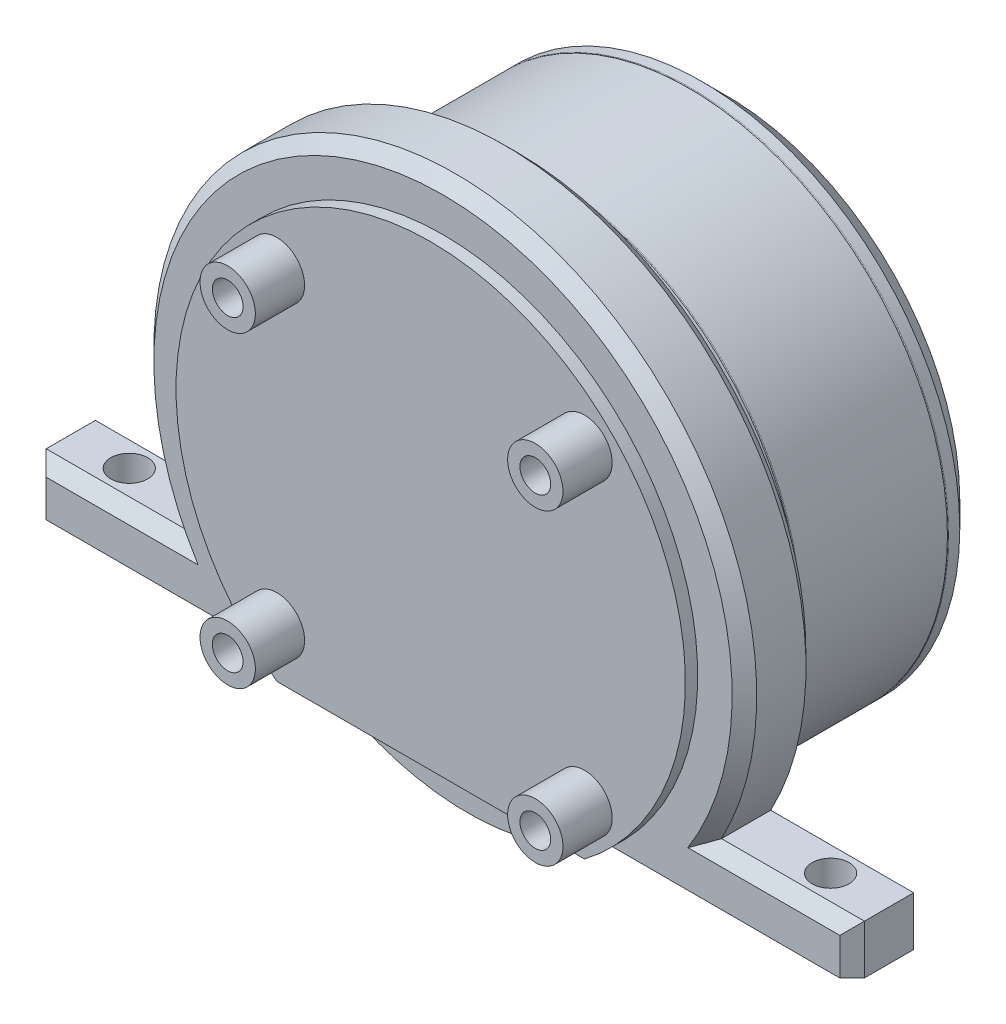
SolidWorks part; units mm, degrees
ref_plane "Front Plane" through (0, 0, 0) normal (0, 0, 1) x (1, 0, 0)
ref_plane "Top Plane" through (0, 0, 0) normal (0, 1, 0) x (1, 0, 0)
ref_plane "Right Plane" through (0, 0, 0) normal (1, 0, 0) x (0, 0, -1)
sketch "Sketch1" plane through (0, 0, 0) normal (0, 0, 1) x (1, 0, 0)
  circle A0 centre (0, 0) radius 21
  dimension "D1" = 42
extrude "Boss-Extrude1" add sketch "Sketch1" along normal blind 3
chamfer "Chamfer1" distance 2 angle 45 1 edges at (21, 0, 0)
fillet "Fillet1" radius 0.1 1 edges at (21, 0, 3)
sketch "Sketch2" plane through (0, 0, 3) normal (0, 0, 1) x (1, 0, 0)
  circle A0 centre (0, 0) radius 21 construction
  circle A1 centre (0, 0) radius 21
extrude "Boss-Extrude2" add sketch "Sketch2" along normal blind 12
fillet "Fillet2" radius 0.1 1 edges at (21, 0, 15)
sketch "Sketch3" plane through (0, 0, 15) normal (0, 0, 1) x (1, 0, 0)
  circle A0 centre (0, 0) radius 21 construction
  circle A1 centre (0, 0) radius 21
extrude "Boss-Extrude3" add sketch "Sketch3" along normal blind 6
sketch "Sketch4" plane through (0, 0, 0) normal (0, 0, -1) x (-1, 0, 0)
  line L0 (-10, 0) -> (0, 0) construction
  circle A0 centre (0, 0) radius 3
  circle A1 centre (-10, 0) radius 1.5
  circle A2 centre (0, 0) radius 3
  circle A3 centre (0, 10) radius 1.5
  circle A4 centre (0, 0) radius 3
  circle A5 centre (10, 0) radius 1.5
  circle A6 centre (0, 0) radius 3
  circle A7 centre (0, -10) radius 1.5
  point P17 (0, 0)
  dimension "D1" = 6
  dimension "D2" = 3
  dimension "D3" = 10
  dimension "D4" = 4
extrude "Cut-Extrude1" cut sketch "Sketch4" against normal blind 6
ref_plane "Plane1" through (0, 0, 17) normal (0, 0, 1) x (1, 0, 0)
sketch "Sketch5" plane through (0, 0, 17) normal (0, 0, 1) x (1, 0, 0)
  line L0 (21.6333, -11.5) -> (33.25, -11.5)
  line L1 (-33.25, -15.5) -> (33.25, -15.5)
  line L2 (-33.25, -15.5) -> (-33.25, -11.5)
  line L3 (-33.25, -11.5) -> (-21.6333, -11.5)
  line L4 (33.25, -15.5) -> (33.25, -11.5)
  line L5 (0, 0) -> (0, -15.5) construction
  arc A0 (21.6333, -11.5) -> (-21.6333, -11.5) centre (0, 0) ccw
  dimension "D1" = 49
  dimension "D2" = 66.5
  dimension "D3" = 4
  dimension "D4" = 15.5
extrude "Boss-Extrude4" add sketch "Sketch5" along normal blind 6
chamfer "Chamfer2" distance 1 angle 45 10 edges at (0, 24.5, 17) (0, 24.5, 23) (-33.25, -13.5, 17) (-27.4417, -11.5, 17) (33.25, -13.5, 17) (27.4417, -11.5, 17) (-33.25, -13.5, 23) (-27.4417, -11.5, 23) (33.25, -13.5, 23) (27.4417, -11.5, 23)
sketch "Sketch6" plane through (0, -11.5, 0) normal (0, 1, 0) x (1, 0, 0)
  line L0 (-28.5, -20) -> (28.5, -20) construction
  line L1 (0, -20) -> (0, 0) construction
  line L2 (19, 0) -> (-19, 0) construction
  line L3 (-23.5, -23) -> (23.5, -23) construction
  circle A0 centre (-28.5, -20) radius 1.5
  circle A1 centre (28.5, -20) radius 1.5
  dimension "D3" = 3
  dimension "D1" = 3
  dimension "D2" = 57
extrude "Cut-Extrude2" cut sketch "Sketch6" against normal through all and the other way through all
sketch "Sketch7" plane through (0, 0, 23) normal (0, 0, 1) x (1, 0, 0)
  line L0 (12.4996, -16.5) -> (-12.4996, -16.5)
  line L1 (-32.25, -15.5) -> (32.25, -15.5) construction
  arc A0 (12.4996, -16.5) -> (-12.4996, -16.5) centre (0, 0) ccw
  dimension "D2" = 20.7
  dimension "D1" = 1
extrude "Boss-Extrude5" add sketch "Sketch7" along normal blind 1
sketch "Sketch8" plane through (0, 0, 24) normal (0, 0, 1) x (1, 0, 0)
  line L1 (-12.5, 12.5) -> (12.5, 12.5) construction
  line L2 (-12.5, 12.5) -> (-12.5, -12.5) construction
  line L3 (-12.5, -12.5) -> (12.5, -12.5) construction
  line L4 (12.5, 12.5) -> (12.5, -12.5) construction
  line L5 (-12.5, 12.5) -> (12.5, -12.5) construction
  line L6 (-12.5, -12.5) -> (12.5, 12.5) construction
  circle A0 centre (-12.5, 12.5) radius 2.25
  circle A1 centre (12.5, 12.5) radius 2.25
  circle A2 centre (12.5, -12.5) radius 2.25
  circle A3 centre (-12.5, -12.5) radius 2.25
  point P0 (0, 0)
  dimension "D2" = 4.5
  dimension "D1" = 25
extrude "Boss-Extrude6" add sketch "Sketch8" along normal blind 4
sketch "Sketch9" plane through (0, 0, 28) normal (0, 0, 1) x (1, 0, 0)
  circle A2 centre (12.5, 12.5) radius 1.25
  circle A3 centre (12.5, 12.5) radius 1.25
  circle A4 centre (12.5, -12.5) radius 1.25
  circle A5 centre (12.5, -12.5) radius 1.25
  circle A8 centre (-12.5, 12.5) radius 1.25
  circle A9 centre (-12.5, 12.5) radius 1.25
  circle A11 centre (-12.5, -12.5) radius 1.25
  circle A12 centre (-12.5, -12.5) radius 1.25
  dimension "D1" = 1
  dimension "D2" = 1
  dimension "D3" = 1
  dimension "D4" = 1
extrude "Cut-Extrude3" cut sketch "Sketch9" against normal blind 4
